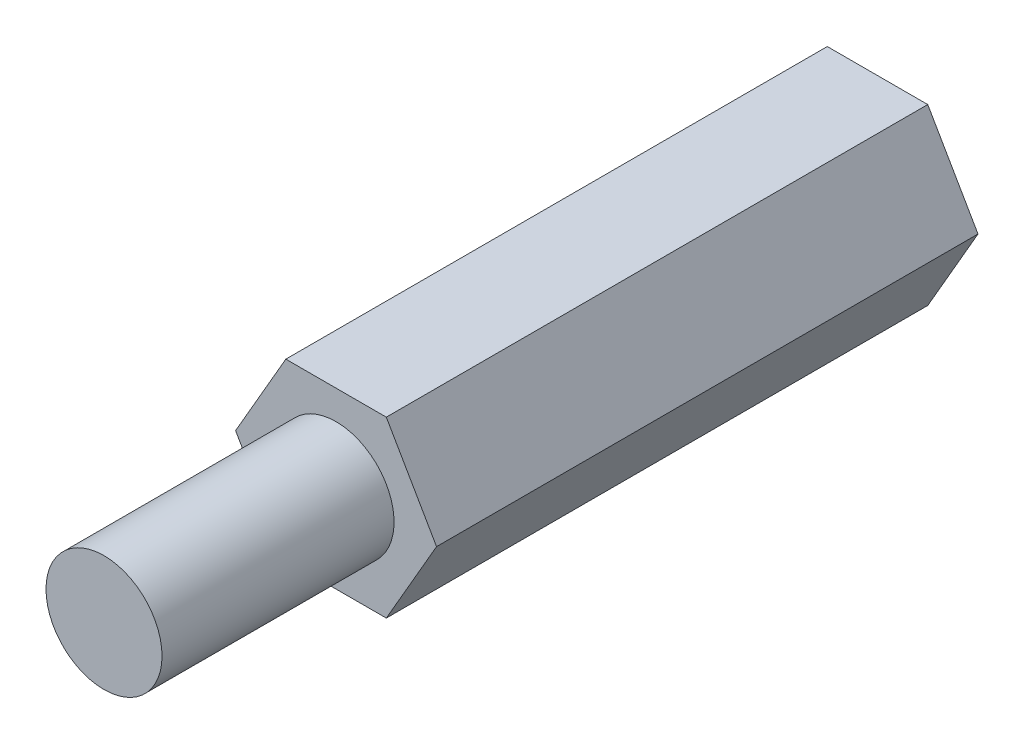
SolidWorks part; units mm, degrees
material "Aluminum"
ref_plane "Front Plane" through (0, 0, 0) normal (0, 0, 1) x (1, 0, 0)
ref_plane "Top Plane" through (0, 0, 0) normal (0, 1, 0) x (1, 0, 0)
ref_plane "Right Plane" through (0, 0, 0) normal (1, 0, 0) x (0, 0, -1)
sketch "Sketch1" plane through (0, 0, 0) normal (0, 0, 1) x (1, 0, 0)
  circle A0 centre (0, 0) radius 1.5
  dimension "D1" = 3
extrude "Boss-Extrude1" add sketch "Sketch1" along normal blind 6
sketch "Sketch2" plane through (0, 0, 0) normal (0, 0, -1) x (-1, 0, 0)
  line L1 (1.299, 2.25) -> (-1.299, 2.25)
  line L2 (-1.299, 2.25) -> (-2.5981, 0)
  line L3 (-2.5981, 0) -> (-1.299, -2.25)
  line L4 (-1.299, -2.25) -> (1.299, -2.25)
  line L5 (1.299, -2.25) -> (2.5981, 0)
  line L6 (2.5981, 0) -> (1.299, 2.25)
  circle A0 centre (0, 0) radius 2.25 construction
  dimension "D1" = 4.5
extrude "Boss-Extrude2" add sketch "Sketch2" along normal blind 14
sketch "Sketch3" plane through (0, 0, -14) normal (0, 0, -1) x (-1, 0, 0)
  circle A0 centre (0, 0) radius 1.5
  dimension "D1" = 3
extrude "Cut-Extrude1" cut sketch "Sketch3" against normal blind 4.5
